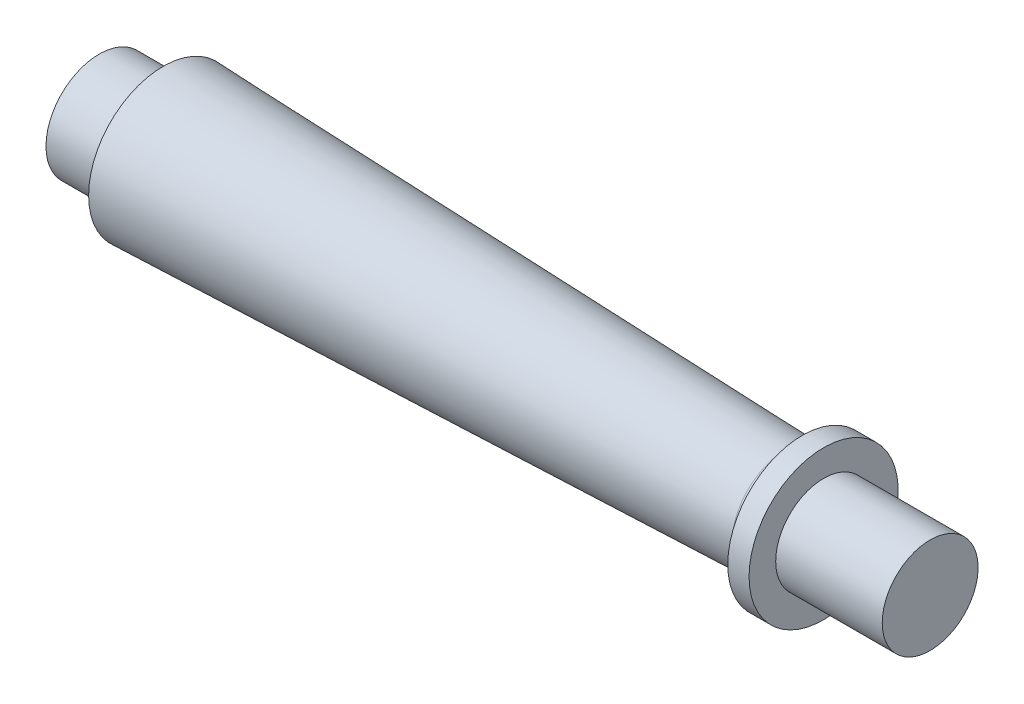
SolidWorks part; units mm, degrees
ref_plane "Front Plane" through (0, 0, 0) normal (0, 0, 1) x (1, 0, 0)
ref_plane "Top Plane" through (0, 0, 0) normal (0, 1, 0) x (1, 0, 0)
ref_plane "Right Plane" through (0, 0, 0) normal (1, 0, 0) x (0, 0, -1)
sketch "Sketch1" plane through (0, 0, 0) normal (0, 0, 1) x (1, 0, 0)
  line L0 (0, 0) -> (78, 0)
  line L1 (78, 0) -> (78, 4.5)
  line L2 (78, 4.5) -> (68, 4.5)
  line L3 (68, 4.5) -> (68, 7)
  line L4 (68, 7) -> (66, 7)
  line L5 (66, 7) -> (66, 5)
  line L6 (66, 5) -> (6, 7)
  line L7 (6, 7) -> (6, 5)
  line L8 (6, 5) -> (0, 5)
  line L9 (0, 5) -> (0, 0)
  dimension "D1" = 4.5
  dimension "D2" = 2
  dimension "D3" = 5
  dimension "D4" = 5
  dimension "D5" = 7
  dimension "D6" = 6
  dimension "D7" = 60
  dimension "D8" = 10
  dimension "D9" = 7
revolve "Revolve1" add sketch "Sketch1" angle 360 about L0
cosmetic thread "Cosmetic Thread2" parameters "D1"=10, "D2"=6.891
cosmetic thread "Cosmetic Thread3" parameters "D1"=6, "D2"=8.619
fillet "Fillet2" radius 1.5 1 edges at (66, 0, 5)
